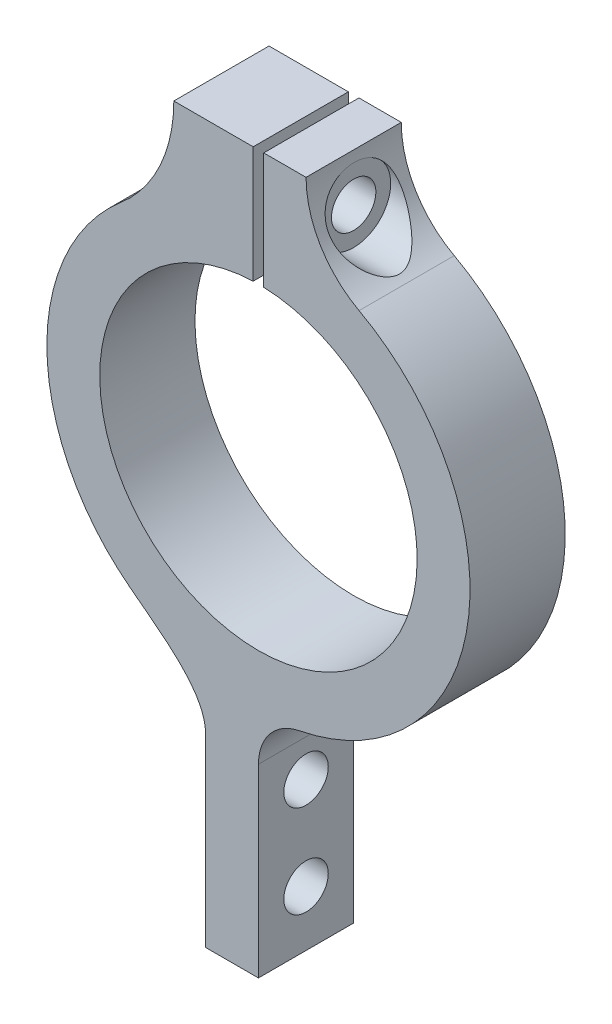
SolidWorks part; units mm, degrees
ref_plane "Front Plane" through (0, 0, 0) normal (0, 0, 1) x (1, 0, 0)
ref_plane "Top Plane" through (0, 0, 0) normal (0, 1, 0) x (1, 0, 0)
ref_plane "Right Plane" through (0, 0, 0) normal (1, 0, 0) x (0, 0, -1)
sketch "Sketch1" plane through (0, 0, 0) normal (0, 0, 1) x (1, 0, 0)
  line L0 (0, 0) -> (0, 40) construction
  line L1 (0, -48.6004) -> (0, -83.6004)
  line L2 (0, -83.6004) -> (-10, -83.6004)
  line L3 (-10, -83.6004) -> (-10, -48.6004)
  line L4 (30, 0) -> (40, 0) construction
  line L6 (0, 40) -> (0, 52) construction
  line L7 (0, 52) -> (1, 52) construction
  line L8 (1, 52) -> (1, 29.9833)
  line L9 (1, 52) -> (9, 52)
  line L11 (0, 52) -> (-1, 52) construction
  line L12 (-1, 52) -> (-1, 29.9833)
  line L13 (-1, 52) -> (-16, 52)
  arc A0 (-1, 29.9833) -> (1, 29.9833) centre (0, 0) ccw
  arc A1 (0, -48.6004) -> (7.6931, -39.2532) centre (9.525, -48.6004) cw
  arc A2 (0, 40) -> (-1, 39.9875) centre (0, 0) ccw construction
  arc A3 (9, 52) -> (19.0232, 35.1869) centre (28.1129, 52) ccw
  arc A4 (-25.9512, 30.439) -> (-26.5352, -29.9313) centre (0, 0) ccw
  circle A5 centre (0, 0) radius 40 construction
  arc A6 (-25.9512, 30.439) -> (-16, 52) centre (-44.3333, 52) ccw
  arc A8 (7.6931, -39.2532) -> (19.0232, 35.1869) centre (0, 0) ccw
  spline S0 degree 3 poles (-26.5352, -29.9313) (-20.9482, -34.8844) (-10, -40.904) (-10, -48.6004) knots 0 0 0 0 1 1 1 1
  point P27 (0, -40)
  dimension "D1" = 60
  dimension "D3" = 35
  dimension "D4" = 10
  dimension "D2" = 10
  dimension "D11" = 9.525
  dimension "D6" = 12
  dimension "D7" = 1
  dimension "D8" = 8
  dimension "D9" = 1
  dimension "D10" = 15
extrude "main body" add sketch "Sketch1" along normal blind 18
sketch "Sketch7" plane through (1, 0, 0) normal (-1, 0, 0) x (0, 0, 1)
  line L3 (9, 43) -> (9, 52) construction
  line L4 (18, 52) -> (0, 52) construction
  line L5 (9, 43) -> (0, 43) construction
  line L6 (0, 52) -> (0, 35.1869) construction
  circle A0 centre (9, 43) radius 4
  dimension "D1" = 8
sketch "Sketch12" plane through (0, 0, 0) normal (1, 0, 0) x (0, 0, -1)
  line L0 (-9, -48.6004) -> (-9, -55.6004) construction
  line L1 (-9, -62.6004) -> (-9, -73.1004) construction
  line L2 (-18, -48.6004) -> (0, -48.6004) construction
  line L3 (-9, -73.1004) -> (-9, -83.6004) construction
  line L4 (-18, -83.6004) -> (0, -83.6004) construction
  circle A0 centre (-9, -55.6004) radius 4
  circle A1 centre (-9, -55.6004) radius 7 construction
  circle A2 centre (-9, -73.1004) radius 4
  circle A3 centre (-9, -73.1004) radius 7 construction
  dimension "D1" = 8
  dimension "D2" = 14
  dimension "D3" = 14
  dimension "D4" = 8
hole_wizard "M8 Clearance Hole1" positions "Sketch13" profile "Sketch14" hole size "M8" standard "ANSI Metric"
sketch "Sketch13" plane through (1, 0, 0) normal (-1, 0, 0) x (0, 0, 1)
  point P0 (9, 43)
sketch "Sketch14" plane through (1, 43, 9) normal (0, 1, 0) x (0, 0, 1)
  line L0 (0, 0) -> (0, 39)
  line L1 (0, 39) -> (4.2, 39)
  line L2 (4.2, 39) -> (4.2, 0)
  line L5 (4.2, 0) -> (0, 0)
  line L11 (0, -6.35) -> (0, 107.95) construction
  dimension "Thru Hole Dia." = 8.4
  dimension "Thru Hole Depth" = 39
hole_wizard "M8 Clearance Hole2" positions "Sketch15" profile "Sketch16" hole size "M8" standard "ANSI Metric" end condition through all
sketch "Sketch15" plane through (1, 0, 0) normal (-1, 0, 0) x (0, 0, 1)
  point P0 (9, 43)
sketch "Sketch16" plane through (1, 43, 9) normal (0, 1, 0) x (0, 0, -1)
  line L0 (0, 0) -> (0, 41)
  line L1 (0, 41) -> (4.2, 41)
  line L2 (4.2, 41) -> (4.2, 0)
  line L5 (4.2, 0) -> (0, 0)
  line L11 (0, -6.35) -> (0, 107.95) construction
  dimension "Thru Hole Dia." = 8.4
  dimension "Thru Hole Depth" = 41
sketch "Sketch17" plane through (0, 0, 18) normal (0, 0, 1) x (1, 0, 0)
  line L0 (-16, 52) -> (-16, 25.3772)
  line L1 (9, 52) -> (9, 28.6182)
  arc A0 (-1, 29.9833) -> (1, 29.9833) centre (0, 0) ccw construction
hole_wizard "M8 Clearance Hole3" positions "Sketch18" profile "Sketch19" hole size "M8" standard "ANSI Metric" end condition through all
sketch "Sketch18" plane through (0, 0, 0) normal (1, 0, 0) x (0, 0, -1)
  point P0 (-9, -55.6004)
  point P3 (-9, -73.1004)
sketch "Sketch19" plane through (0, -55.6004, 9) normal (0, 1, 0) x (0, 0, -1)
  line L0 (0, 0) -> (0, 40)
  line L1 (0, 40) -> (4.2, 40)
  line L2 (4.2, 40) -> (4.2, 0)
  line L5 (4.2, 0) -> (0, 0)
  line L11 (0, -6.35) -> (0, 107.95) construction
  dimension "Thru Hole Dia." = 8.4
  dimension "Thru Hole Depth" = 40
ref_plane "Plane1" through (-16, 0, 0) normal (-1, 0, 0) x (0, 0, 1)
sketch "Sketch26" plane through (-16, 0, 0) normal (-1, 0, 0) x (0, 0, 1)
  circle A0 centre (9, 43) radius 7
  dimension "D1" = 14
ref_plane "Plane2" through (9, 0, 0) normal (1, 0, 0) x (0, 0, -1)
sketch "Sketch27" plane through (9, 0, 0) normal (1, 0, 0) x (0, 0, -1)
  circle A0 centre (-9, 43) radius 7
  circle A1 centre (-9, 43) radius 7 construction
extrude "Cut-Extrude2" cut sketch "Sketch27" along normal through all
